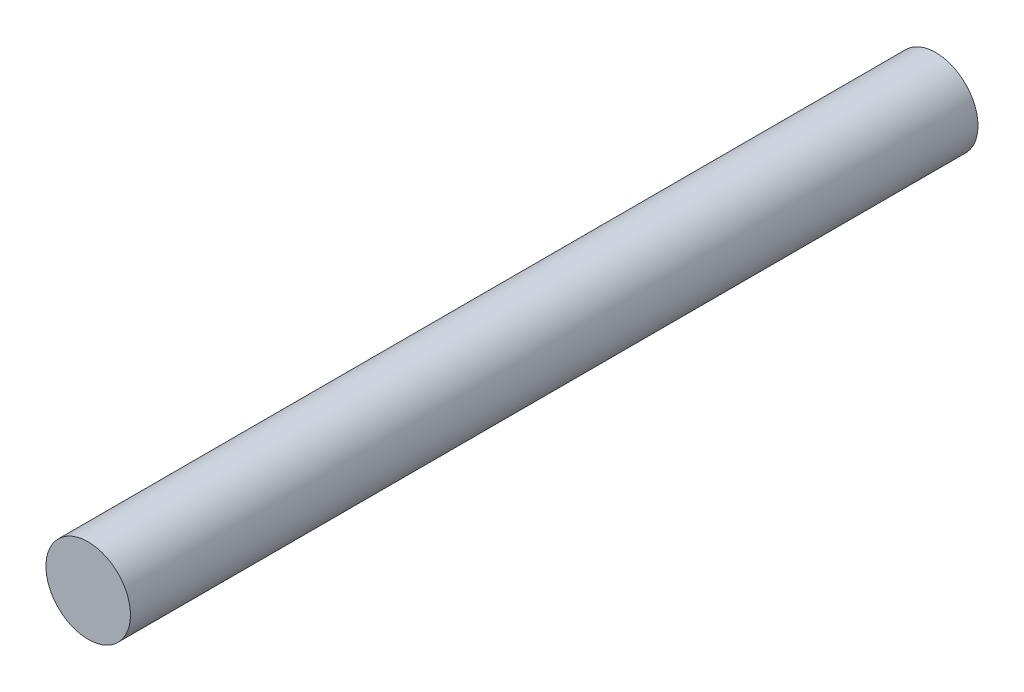
SolidWorks part; units mm, degrees
ref_plane "Front Plane" through (0, 0, 0) normal (0, 0, 1) x (1, 0, 0)
ref_plane "Top Plane" through (0, 0, 0) normal (0, 1, 0) x (1, 0, 0)
ref_plane "Right Plane" through (0, 0, 0) normal (1, 0, 0) x (0, 0, -1)
sketch "Sketch1" plane through (0, 0, 0) normal (0, 0, 1) x (1, 0, 0)
  circle A0 centre (0, 0) radius 99.7465
  dimension "D1" = 199.493
extrude "Boss-Extrude1" add sketch "Sketch1" along normal blind 2000
